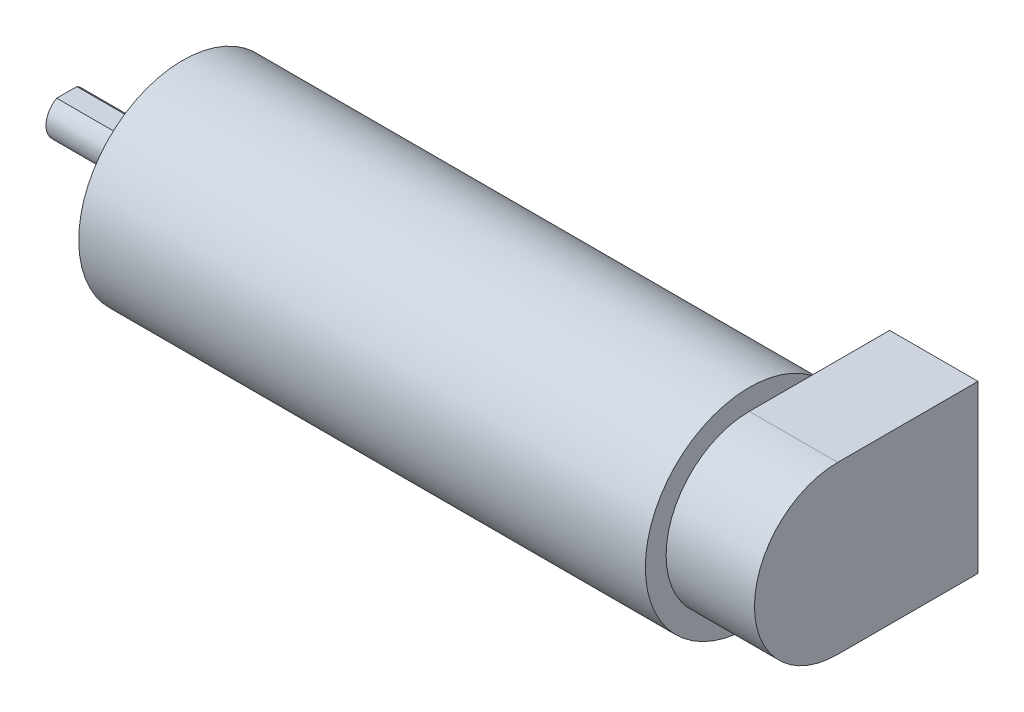
SolidWorks part; units mm, degrees
ref_plane "前视基准面" through (0, 0, 0) normal (0, 0, 1) x (1, 0, 0)
ref_plane "上视基准面" through (0, 0, 0) normal (0, 1, 0) x (1, 0, 0)
ref_plane "右视基准面" through (0, 0, 0) normal (1, 0, 0) x (0, 0, -1)
sketch "草图2" plane through (0, 0, 0) normal (1, 0, 0) x (0, 0, -1)
  circle A0 centre (0, 0) radius 20
  dimension "D1" = 40
extrude "凸台-拉伸1" add sketch "草图2" along normal blind 109
sketch "草图4" plane through (109, 0, 0) normal (1, 0, 0) x (0, 0, -1)
  line L1 (0, 16) -> (27, 16)
  line L3 (0, -16) -> (27, -16)
  line L4 (27, 16) -> (27, -16)
  arc A0 (0, 16) -> (0, -16) centre (0, 0) ccw
  dimension "D1" = 32
  dimension "D2" = 27
extrude "凸台-拉伸2" add sketch "草图4" along normal blind 17
sketch "草图5" plane through (0, 0, 0) normal (-1, 0, 0) x (0, 0, 1)
  circle A0 centre (0, 0) radius 12.5
  dimension "D1" = 25
extrude "凸台-拉伸3" add sketch "草图5" along normal blind 3.3
sketch "草图6" plane through (-3.3, 0, 0) normal (-1, 0, 0) x (0, 0, 1)
  circle A0 centre (0, 0) radius 4
  dimension "D1" = 8
extrude "凸台-拉伸4" add sketch "草图6" along normal blind 19
sketch "草图7" plane through (-22.3, 0, 0) normal (-1, 0, 0) x (0, 0, 1)
  line L0 (1.9365, 3.5) -> (-1.9365, 3.5)
  circle A0 centre (0, 0) radius 4
  circle M2 centre (0, 0) radius 4
  dimension "D1" = 8
  dimension "D2" = 3.5
extrude "切除-拉伸1" cut sketch "草图7" against normal blind 15 contours L0 M2
